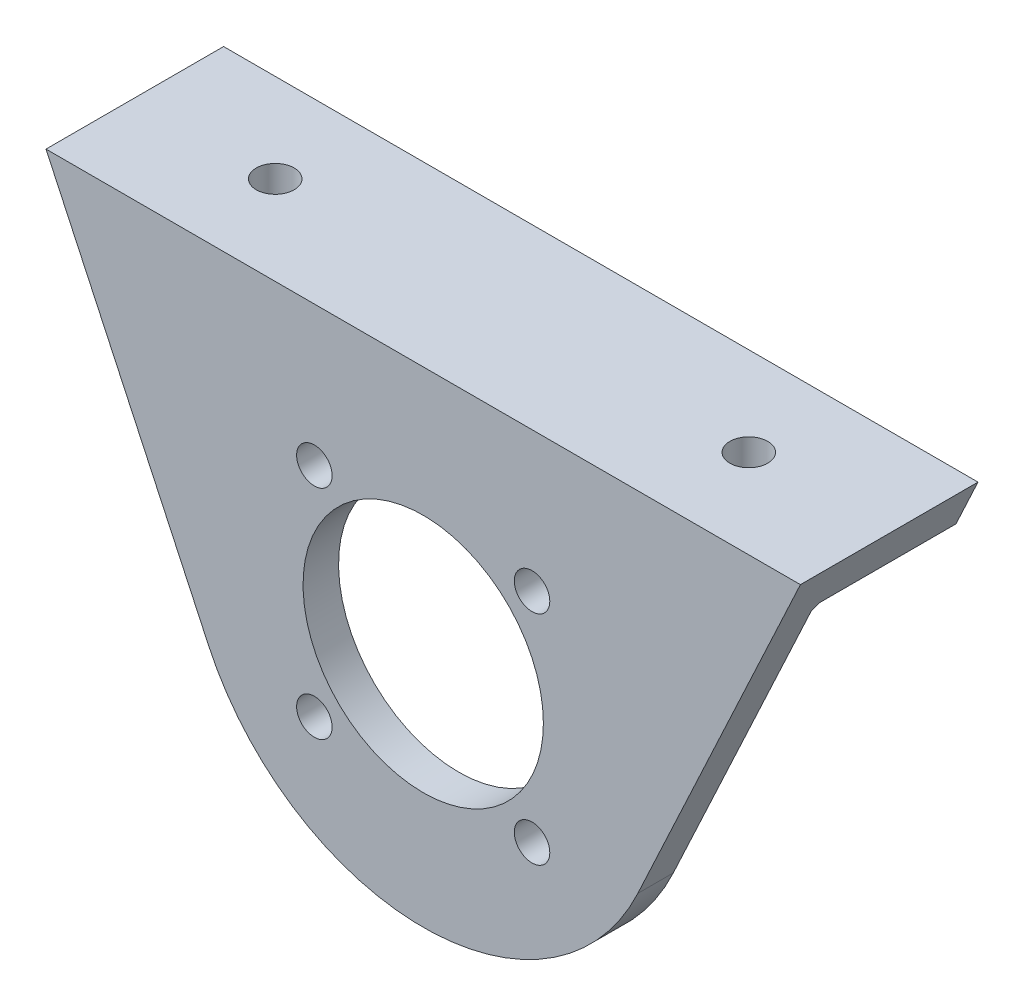
SolidWorks part; units mm, degrees
ref_plane "正面" through (0, 0, 0) normal (0, 0, 1) x (1, 0, 0)
ref_plane "平面" through (0, 0, 0) normal (0, 1, 0) x (1, 0, 0)
ref_plane "右側面" through (0, 0, 0) normal (1, 0, 0) x (0, 0, -1)
sketch "ｽｹｯﾁ1" plane through (0, 0, 0) normal (0, 0, 1) x (1, 0, 0)
  line L0 (-9.1924, 9.1924) -> (9.1924, 9.1924) construction
  line L1 (9.1924, 9.1924) -> (9.1924, -9.1924) construction
  line L2 (9.1924, -9.1924) -> (-9.1924, -9.1924) construction
  line L3 (-9.1924, -9.1924) -> (-9.1924, 9.1924) construction
  line L4 (-9.1924, 9.1924) -> (9.1924, -9.1924) construction
  line L5 (9.1924, 9.1924) -> (-9.1924, -9.1924) construction
  line L6 (-18.1262, -8.4524) -> (-31.86, 21)
  line L7 (-31.86, 21) -> (31.86, 21)
  line L8 (18.1262, -8.4524) -> (31.86, 21)
  line L9 (-18.1262, -8.4524) -> (-18.1262, 21) construction
  line L10 (18.1262, -8.4524) -> (18.1262, 21) construction
  line L11 (0, 16) -> (0, 21) construction
  circle A0 centre (0, 0) radius 10.15
  arc A1 (-18.1262, -8.4524) -> (18.1262, -8.4524) centre (0, 0) ccw
  circle A2 centre (-9.1924, 9.1924) radius 1.5
  circle A3 centre (9.1924, 9.1924) radius 1.5
  circle A4 centre (-9.1924, -9.1924) radius 1.5
  circle A5 centre (9.1924, -9.1924) radius 1.5
  circle A6 centre (0, 0) radius 16 construction
  point P8 (0, 0)
  dimension "D1" = 20.3
  dimension "D3" = 3
  dimension "D4" = 40
  dimension "D5" = 32
  dimension "D2" = 26
  dimension "D6" = 5
  dimension "D7" = 65
extrude "ﾎﾞｽ - 押し出し1" add sketch "ｽｹｯﾁ1" along normal blind 15
sketch "ｽｹｯﾁ2" plane through (0, 0, 0) normal (1, 0, 0) x (0, 0, -1)
  line L0 (0, -8.4524) -> (0, 21) construction
  line L1 (0, 18) -> (-12, 18)
  line L2 (0, 18) -> (0, -20)
  line L3 (0, -20) -> (-12, -20)
  line L4 (-12, 18) -> (-12, -20)
  line L5 (-15, -20) -> (0, -20) construction
  line L6 (-15, -8.4524) -> (-15, 21) construction
  line L7 (-15, 21) -> (0, 21) construction
  dimension "D1" = 3
  dimension "D2" = 3
extrude "ｶｯﾄ - 押し出し1" cut sketch "ｽｹｯﾁ2" against normal mid plane 60
chamfer "面取り1" distance 1.5 angle 45 1 edges at (0, 18, 12)
sketch "ｽｹｯﾁ3" plane through (0, 21, 0) normal (0, 1, 0) x (1, 0, 0)
  line L0 (-31.86, -7.5) -> (-20, -7.5) construction
  line L1 (-31.86, -15) -> (-31.86, 0) construction
  line L2 (-20, -7.5) -> (20, -7.5) construction
  line L3 (20, -7.5) -> (31.86, -7.5) construction
  line L4 (31.86, -15) -> (31.86, 0) construction
  circle A0 centre (-20, -7.5) radius 1.6
  circle A1 centre (20, -7.5) radius 1.6
  dimension "D1" = 3.2
  dimension "D2" = 40
extrude "ｶｯﾄ - 押し出し2" cut sketch "ｽｹｯﾁ3" against normal up to next
